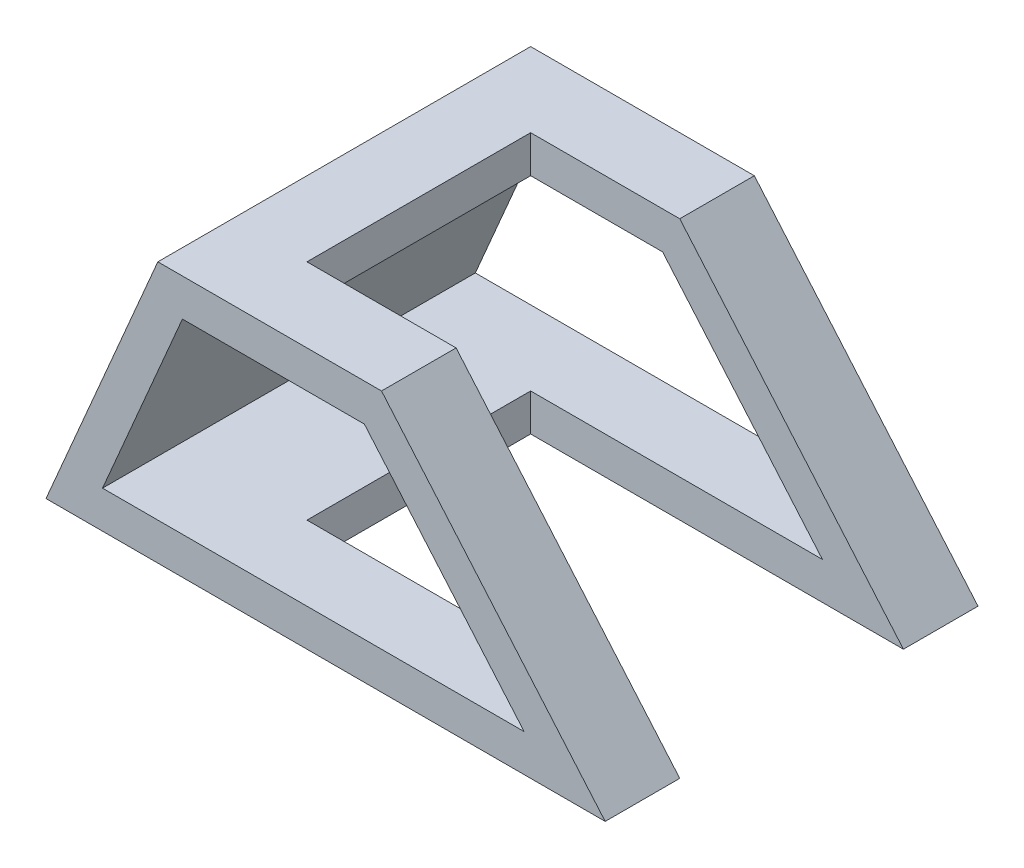
SolidWorks part; units mm, degrees
ref_plane "Front Plane" through (0, 0, 0) normal (0, 0, 1) x (1, 0, 0)
ref_plane "Top Plane" through (0, 0, 0) normal (0, 1, 0) x (1, 0, 0)
ref_plane "Right Plane" through (0, 0, 0) normal (1, 0, 0) x (0, 0, -1)
sketch "Sketch1" plane through (0, 0, 0) normal (0, 0, 1) x (1, 0, 0)
  line L0 (0, 0) -> (150, 0)
  line L1 (150, 0) -> (90, 70)
  line L2 (90, 70) -> (30, 70)
  line L3 (30, 70) -> (0, 0)
  line L4 (36.594, 60) -> (15.1654, 10)
  line L5 (15.1654, 10) -> (128.2578, 10)
  line L6 (128.2578, 10) -> (85.4007, 60)
  line L7 (85.4007, 60) -> (36.594, 60)
  dimension "D1" = 70
  dimension "D2" = 150
  dimension "D3" = 60
  dimension "D4" = 30
  dimension "D5" = 60
  dimension "D6" = 10
extrude "Boss-Extrude2" add sketch "Sketch1" along normal blind 100
sketch "Sketch4" plane through (0, 70, 0) normal (0, 1, 0) x (1, 0, 0)
  line L0 (90, -20) -> (50, -20)
  line L1 (90, -100) -> (90, 0) construction
  line L2 (50, -20) -> (50, -80)
  line L3 (50, -80) -> (90, -80)
  line L4 (90, -80) -> (90, -20)
  line L5 (90, 0) -> (30, 0) construction
  line L6 (90, -100) -> (30, -100) construction
  dimension "D1" = 60
  dimension "D2" = 40
  dimension "D3" = 20
  dimension "D4" = 20
extrude "Cut-Extrude2" cut sketch "Sketch4" against normal blind 100
sketch "Sketch6" plane through (86.4706, 74.1176, 0) normal (0.7593, 0.6508, 0) x (0, 0, -1)
  line L0 (-80, -5.4233) -> (-80, -97.6187)
  line L1 (-80, -5.4233) -> (-20, -5.4233) construction
  line L2 (-100, -97.6187) -> (0, -97.6187) construction
  line L3 (-80, -97.6187) -> (-20, -97.6187)
  line L4 (-20, -97.6187) -> (-20, -5.4233)
  line L5 (-20, -5.4233) -> (-80, -5.4233)
  line L6 (-100, -97.6187) -> (-100, -5.4233) construction
  dimension "D1" = 60
  dimension "D2" = 20
extrude "Cut-Extrude4" cut sketch "Sketch6" against normal blind 57
